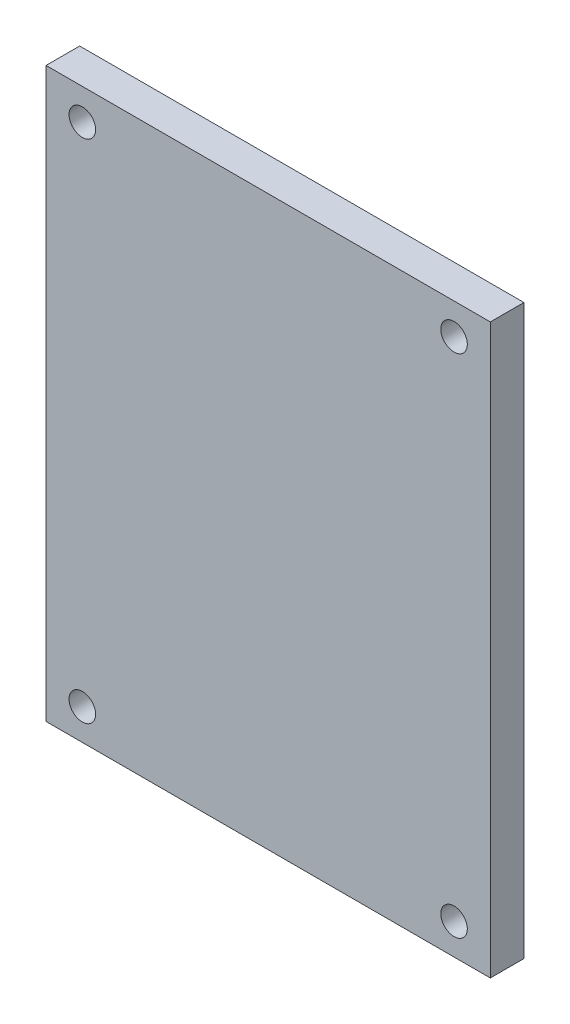
SolidWorks part; units mm, degrees
ref_plane "Front Plane" through (0, 0, 0) normal (0, 0, 1) x (1, 0, 0)
ref_plane "Top Plane" through (0, 0, 0) normal (0, 1, 0) x (1, 0, 0)
ref_plane "Right Plane" through (0, 0, 0) normal (1, 0, 0) x (0, 0, -1)
sketch "Sketch1" plane through (0, 0, 0) normal (0, 0, 1) x (1, 0, 0)
  line L0 (0, 40.767) -> (63.754, 40.767) construction
  line L1 (0, 0) -> (63.754, 0)
  line L2 (0, 0) -> (0, 81.534)
  line L3 (0, 81.534) -> (63.754, 81.534)
  line L4 (63.754, 0) -> (63.754, 81.534)
  line L5 (31.877, 81.534) -> (31.877, 0) construction
  circle A0 centre (5.207, 77.089) radius 1.905
  circle A1 centre (58.547, 77.089) radius 1.905
  circle A2 centre (5.207, 4.445) radius 1.905
  circle A3 centre (58.547, 4.445) radius 1.905
  dimension "D3" = 3.81
  dimension "D4" = 3.81
  dimension "D5" = 3.81
  dimension "D6" = 3.81
  dimension "D1" = 81.534
  dimension "D2" = 63.754
  dimension "D7" = 72.644
  dimension "D8" = 53.34
  dimension "D9" = 53.34
  dimension "D10" = 72.644
  dimension "D11" = 36.322
  dimension "D12" = 26.67
extrude "Boss-Extrude1" add sketch "Sketch1" along normal blind 4.826
equation "\"MDF\"= 0.19in"
equation "\"PVCID\" = 2.067in"
equation "\"PVCOD\" = 2.375in"
equation "\"GenDiameter\"= 60mm"
equation "\"GenCutDiameter\" = 1.8in"
equation "\"GenCutDistance\" = 1"
equation "\"TowerHeight\" = 6in"
equation "\"TowerFrontBase\" = 3in"
equation "\"FunnelHeight\" = 1in"
equation "\"FunnelAngle\" = 20"
equation "\"TowerSideBase\" = 3in"
equation "\"TowerPanelLength\" = 2in"
equation "\"TowerPanelLeeway\" = 0.5in"
equation "\"BaseLength\" = 9in"
equation "\"BaseWidth\" = 10in"
equation "\"WheelHoleLength\" = 3.25in"
equation "\"WheelHoleWidth\" = 26mm"
equation "\"WheelHoleFromBack\" = 1.5in"
equation "\"DropLength\" = 1in"
equation "\"DropWidth\" = 8.5in"
equation "\"BumperWidth\" = 1in"
equation "\"SmallHexDiameter\" = 0.185in"
equation "\"SmallHexHeight\" = 0.701in"
equation "\"ScrewSize\" = 0.106in"
equation "\"BigHexDiameter\" = 0.251in"
equation "\"BigHexHeight\" = 0.374in"
equation "\"PCBThickness\" = 0.066in"
equation "\"ConnectorHeight\" = 0.517in"
equation "\"BoardHeight\" = 0.583in"
equation "\"UnoStackHeight\" = 1.351in"
equation "\"UnoStackWidth\" = 3.053in"
equation "\"UnoStackLength\" = 3.152in"
equation "\"HBridgeWidth\" = 1.797in"
equation "\"HBridgeLength\" = 2.236in"
equation "\"DSWidth\" = 1.820in"
equation "\"DSLength\" = 1.833in"
equation "\"StepperWidth\" = 1.799in"
equation "\"StepperLength\" = 2.248in"
equation "\"ULNWidth\" = 1.304in"
equation "\"ULNLength\" = 1.545in"
equation "\"VSwitchHeight\" = 0.392in"
equation "\"VSwitchWidth\" = 0.637in"
equation "\"VSwitchLength\" = 1.097in"
equation "\"SkateWheelDiameter\" = 80mm"
equation "\"SkateWheelThickness\" = 24mm"
equation "\"BaseDistance\" = 3in"
equation "\"DummyVar\" = 2in"
equation "\"D1@Boss-Extrude1\"=\"MDF\""
